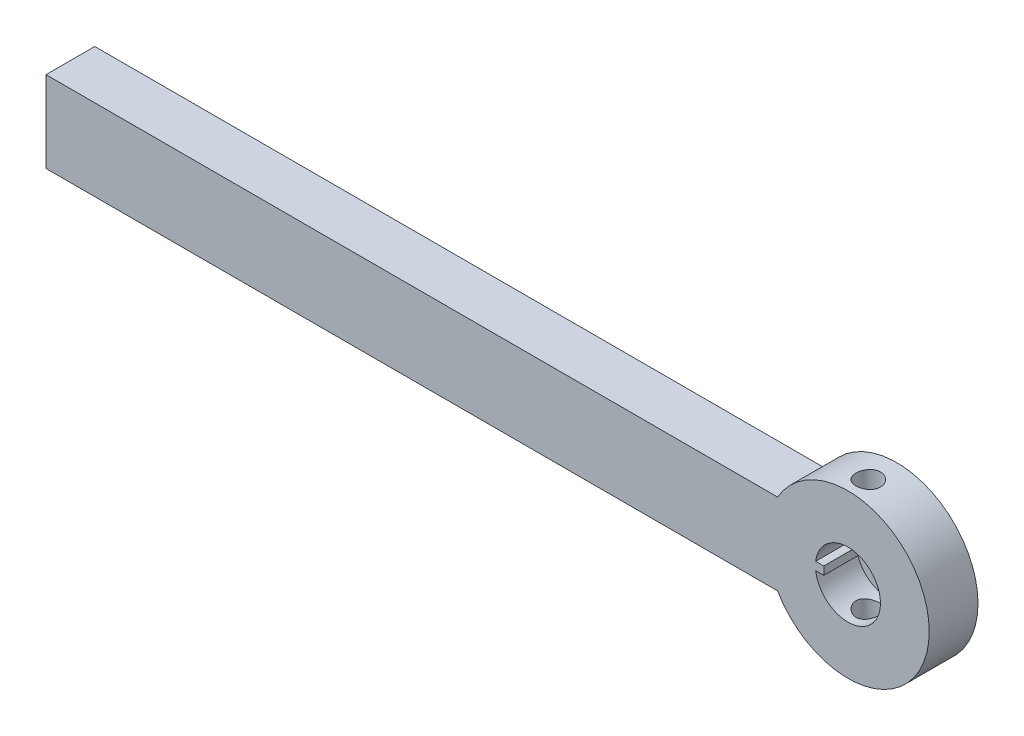
SolidWorks part; units mm, degrees
ref_plane "Front Plane" through (0, 0, 0) normal (0, 0, 1) x (1, 0, 0)
ref_plane "Top Plane" through (0, 0, 0) normal (0, 1, 0) x (1, 0, 0)
ref_plane "Right Plane" through (0, 0, 0) normal (1, 0, 0) x (0, 0, -1)
sketch "Sketch1" plane through (0, 0, 0) normal (0, 0, 1) x (1, 0, 0)
  line L1 (-98.6603, 5) -> (-8.6603, 5)
  line L2 (-98.6603, 5) -> (-98.6603, -5)
  line L3 (-98.6603, -5) -> (-8.6603, -5)
  arc A0 (-8.6603, -5) -> (-8.6603, 5) centre (0, 0) ccw
  dimension "D1" = 20
  dimension "D2" = 10
  dimension "D3" = 5
  dimension "D4" = 90
extrude "Boss-Extrude1" add sketch "Sketch1" along normal blind 6
sketch "Sketch2" plane through (0, 0, 6) normal (0, 0, 1) x (1, 0, 0)
  circle A0 centre (0, 0) radius 4
  dimension "D1" = 8
extrude "Cut-Extrude1" cut sketch "Sketch2" against normal blind 5
ref_plane "Plane1" through (0, -10, 0) normal (0, -1, 0) x (-1, 0, 0)
sketch "Sketch3" plane through (0, -10, 0) normal (0, -1, 0) x (-1, 0, 0)
  line L0 (-10, -6) -> (8.6603, -6) construction
  line L1 (8.6603, -6) -> (8.6603, 0) construction
  circle A0 centre (0, -3.5) radius 1.5
  dimension "D1" = 3
  dimension "D2" = 2.5
  dimension "D3" = 8.6603
extrude "Cut-Extrude2" cut sketch "Sketch3" against normal blind 24
sketch "Sketch4" plane through (0, 0, 6) normal (0, 0, 1) x (1, 0, 0)
  line L0 (-4.782, 0) -> (5.8471, 0) construction
  line L1 (-3.9686, 0.5) -> (-2.9686, 0.5)
  line L2 (-2.9686, 0.5) -> (-2.9686, -0.5)
  line L3 (-2.9686, -0.5) -> (-3.9686, -0.5)
  circle A0 centre (0, 0) radius 4 construction
  arc A1 (-3.9686, 0.5) -> (-3.9686, -0.5) centre (0, 0) ccw
  dimension "D1" = 0.5
  dimension "D2" = 0.5
  dimension "D3" = 1
extrude "Boss-Extrude2" add sketch "Sketch4" against normal up to surface (5 mm away) up to face at (4, 0, 1)
